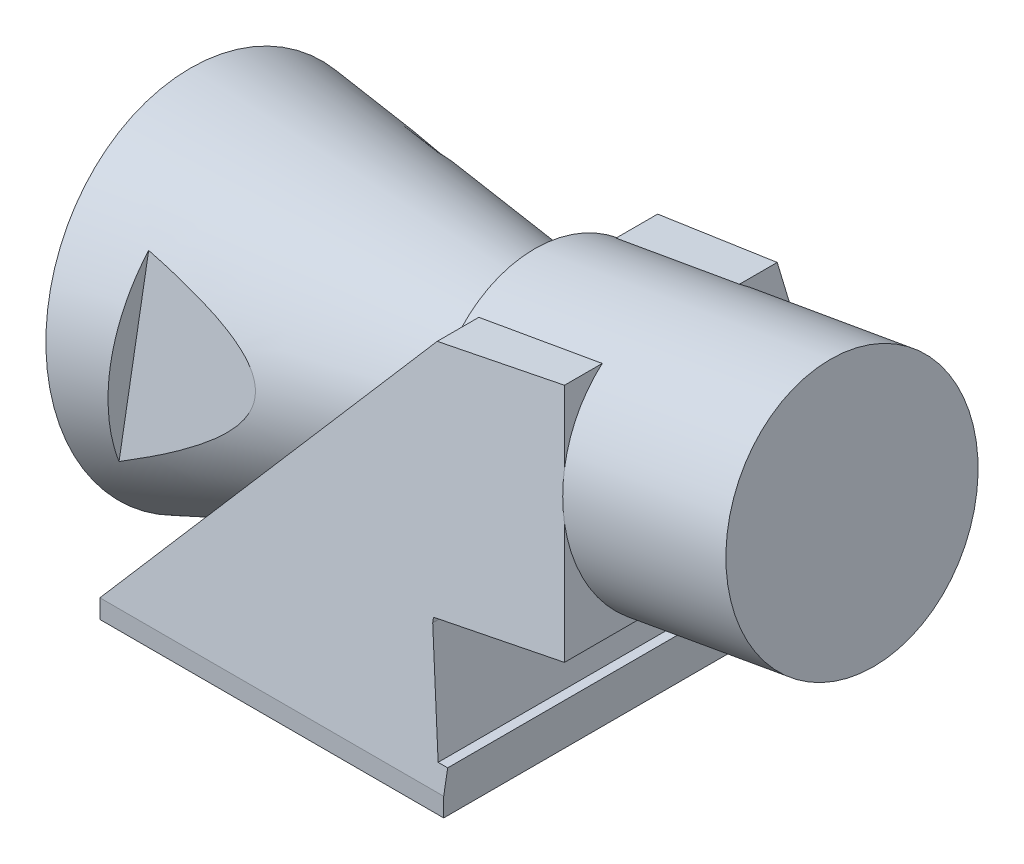
SolidWorks part; units mm, degrees
ref_plane "前视基准面" through (0, 0, 0) normal (0, 0, 1) x (1, 0, 0)
ref_plane "上视基准面" through (0, 0, 0) normal (0, 1, 0) x (1, 0, 0)
ref_plane "右视基准面" through (0, 0, 0) normal (1, 0, 0) x (0, 0, -1)
sketch "草图1" plane through (0, 0, 0) normal (0, 0, 1) x (1, 0, 0)
  line L0 (0, 0) -> (83, 0)
  line L1 (41.5, 0) -> (41.5, 54) construction
  line L2 (0, 0) -> (0, 54) construction
  line L3 (0, 54) -> (83, 54) construction
  line L4 (83, 54) -> (83, 0) construction
  line L5 (41.5, 54) -> (0, 4.5422) construction
  line L6 (-4.4732, 3.7535) -> (-18.886, 85.4925)
  line L7 (-11.6796, 44.623) -> (101.5733, 64.5925) construction
  line L8 (98.9686, 79.3647) -> (104.178, 49.8204) construction
  line L9 (1.443, 6.2619) -> (64.2962, 81.1674) construction
  line L10 (-18.886, 85.4925) -> (98.9686, 79.3647) construction
  line L11 (-4.4732, 3.7535) -> (104.178, 49.8204) construction
  line L12 (64.2962, 81.1674) -> (68.2547, 58.7176) construction
  line L13 (64.2962, 81.1674) -> (72.2132, 36.2677) construction
  dimension "D1" = 83
  dimension "D2" = 50
  dimension "D3" = 54
  dimension "D4" = 30
  dimension "D5" = 115
  dimension "D6" = 61
  dimension "D7" = 33.8326
  dimension "D8" = 41.5
sketch "草图2" plane through (0, 0, 0) normal (0, 0, 1) x (1, 0, 0)
  line L0 (0, 0) -> (83, 0)
  line L1 (83, 0) -> (75.1105, 34.2376)
  line L2 (75.1105, 34.2376) -> (75.1105, 35.3238)
  line L3 (75.1105, 35.3238) -> (105.7806, 40.7317)
  line L4 (105.7806, 40.7317) -> (97.0938, 89.9968)
  line L5 (97.0938, 89.9968) -> (67.2962, 84.7427)
  line L6 (67.2962, 84.7427) -> (0, 4.5422)
  line L7 (0, 4.5422) -> (0, 0)
  line L8 (1.443, 6.2619) -> (64.2962, 81.1674) construction
  line L10 (98.9686, 79.3647) -> (104.178, 49.8204) construction
  line L11 (-4.4732, 3.7535) -> (104.178, 49.8204) construction
  dimension "D1" = 2
  dimension "D2" = 3
  dimension "D3" = 3
extrude "凸台-拉伸1" add sketch "草图2" along normal blind 81.5
sketch "草图3" plane through (109.5564, 19.3178, 0) normal (0.9848, 0.1736, 0) x (0, 0, -1)
  line L0 (-81.5, 71.7694) -> (0, 21.7443) construction
  circle A0 centre (-40.75, 46.7569) radius 30
  dimension "D1" = 60
extrude "凸台-拉伸2" add sketch "草图3" along normal blind 40 and the other way blind 32.5
sketch "草图4" plane through (0, 0, 81.5) normal (0, 0, 1) x (1, 0, 0)
  line L0 (83, 0) -> (83, 10)
  line L1 (83, 54) -> (83, 0) construction
  line L2 (83, 10) -> (80.6957, 10)
  line L3 (83, 0) -> (75.1105, 34.2376) construction
  line L4 (80.6957, 10) -> (83, 0)
  dimension "D1" = 10
extrude "凸台-拉伸3" add sketch "草图4" against normal up to surface (81.5 mm away) up to face at (62.9239, 36.1969, 0)
ref_plane "基准面1" through (0, 0, 40.75) normal (0, 0, -1) x (-1, 0, 0)
sketch "草图5" plane through (0, 0, 40.75) normal (0, 0, 1) x (1, 0, 0)
  line L0 (-11.6796, 44.623) -> (-18.886, 85.4925)
  line L1 (-18.886, 85.4925) -> (98.9686, 79.3647)
  line L2 (98.9686, 79.3647) -> (101.5733, 64.5925)
  line L3 (101.5733, 64.5925) -> (-11.6796, 44.623)
revolve "旋转1" add sketch "草图5" angle 360 about L3
sketch "草图6" plane through (-2.2366, 1.8767, 0) normal (-0.766, 0.6428, 0) x (0, 0, 1)
  spline S0 degree 3 poles (40.75, 5.7244) (101.1867, 5.7244) (101.1867, 103.5067) (40.75, 103.5067) (-19.6867, 103.5067) (-19.6867, 5.7244) (40.75, 5.7244) (101.1867, 5.7244) (101.1867, 103.5067) knots -0.5 0 0 0 0.5 0.5 0.5 1 1 1 1.5 1.5 1.5 weights 1 0.333333 0.333333 1 0.333333 0.333333 1 0.333333 0.333333 only from (40.75, 5.7244) to (40.75, 5.7244)
  spline S1 degree 3 poles (40.75, 5.7244) (101.1867, 5.7244) (101.1867, 103.5067) (40.75, 103.5067) (-19.6867, 103.5067) (-19.6867, 5.7244) (40.75, 5.7244) (101.1867, 5.7244) (101.1867, 103.5067) knots -0.5 0 0 0 0.5 0.5 0.5 1 1 1 1.5 1.5 1.5 weights 1 0.333333 0.333333 1 0.333333 0.333333 1 0.333333 0.333333 only from (40.75, 5.7244) to (40.75, 5.7244) construction
sketch "草图7" plane through (0, 0, 0) normal (-1, 0, 0) x (0, 0, 1)
  line L0 (0, 4.5422) -> (15.068, 89.9968)
  line L1 (24.1858, 89.9968) -> (0, 89.9968) construction
  line L2 (15.068, 89.9968) -> (0, 89.9968)
  line L3 (0, 89.9968) -> (0, 4.5422)
  line L4 (40.75, 0) -> (40.75, 101.8544) construction
  line L5 (81.5, 0) -> (0, 0) construction
  line L6 (40.75, 2.4982) -> (40.75, -2.4982) construction
  line L7 (81.5, 89.9968) -> (81.5, 4.5422)
  line L8 (66.432, 89.9968) -> (81.5, 89.9968)
  line L9 (81.5, 4.5422) -> (66.432, 89.9968)
  ellipse E0 centre (40.75, 72.3102) end of major axis (70.75, 72.3102) minor radius 29.5442 construction
  dimension "D1" = 10
extrude "切除-拉伸1" cut sketch "草图7" against normal up to surface (97.0938 mm away)
sketch "草图8" plane through (0, 0, 0) normal (0, 0, 1) x (1, 0, 0)
  line L0 (80.6957, 10) -> (64.2962, 81.1674) construction
  line L1 (75.1105, 34.2376) -> (80.6957, 10) construction
  line L2 (-11.6796, 44.623) -> (101.5733, 64.5925) construction
  line L3 (1.443, 6.2619) -> (64.2962, 81.1674) construction
  point P7 (69.422, 58.9234)
  dimension "D1" = 28.3527
  dimension "D2" = 127.024
